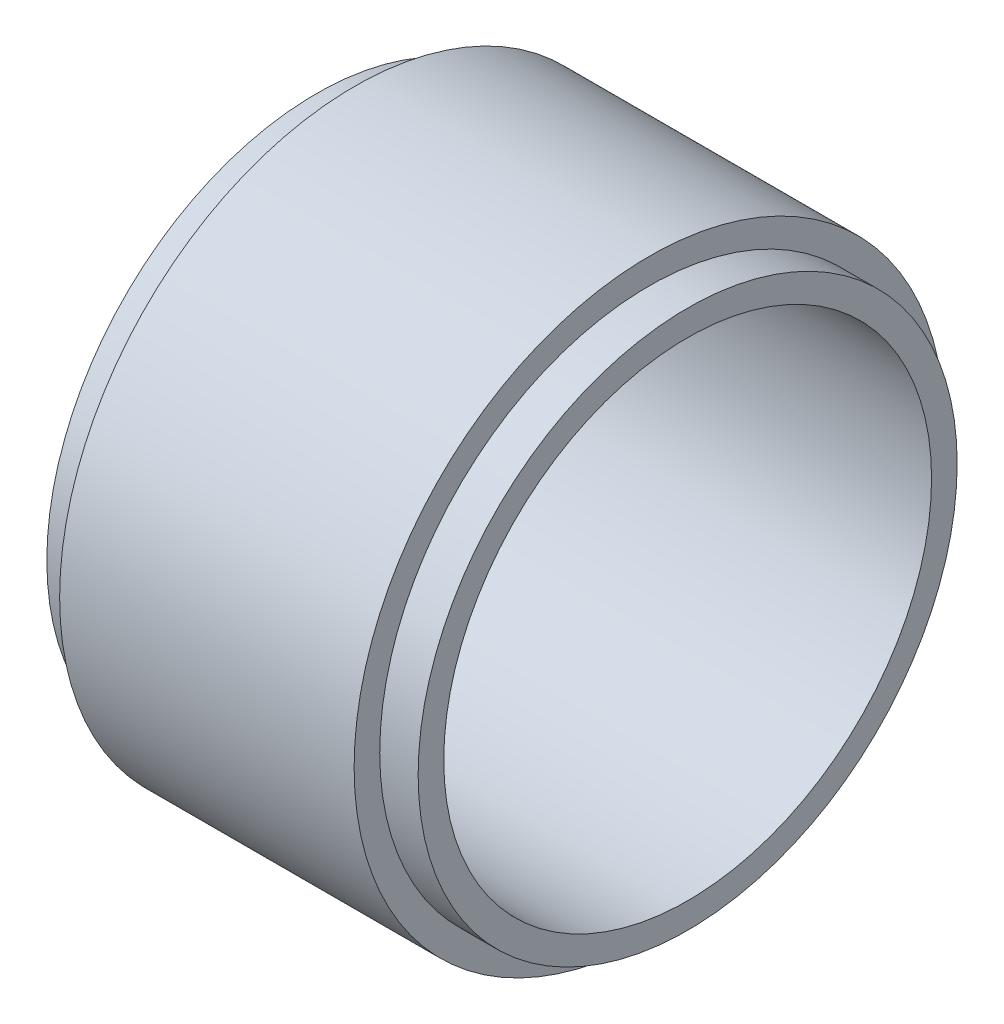
SolidWorks part; units mm, degrees
material "5052-H32"
ref_plane "Front Plane" through (0, 0, 0) normal (0, 0, 1) x (1, 0, 0)
ref_plane "Top Plane" through (0, 0, 0) normal (0, 1, 0) x (1, 0, 0)
ref_plane "Right Plane" through (0, 0, 0) normal (1, 0, 0) x (0, 0, -1)
sketch "Sketch2" plane through (0, 0, 0) normal (0, 0, 1) x (1, 0, 0)
  line L0 (0, 21.05) -> (-3, 21.05)
  line L1 (-3, 21.05) -> (-3, 23.05)
  line L2 (-3, 23.05) -> (-26, 23.05)
  line L3 (-26, 23.05) -> (-26, 21.05)
  line L4 (-26, 21.05) -> (-29, 21.05)
  line L5 (-29, 21.05) -> (-29, 19.05)
  line L6 (-29, 19.05) -> (0, 19.05)
  line L7 (0, 19.05) -> (0, 21.05)
  line L8 (0, 0) -> (-23, 0) construction
  line L9 (0, -22.5996) -> (0, 22.5996) construction
  point P16 (0, 0)
  dimension "D1" = 19.05
  dimension "D2" = 2
  dimension "D3" = 4
  dimension "D4" = 3
  dimension "D5" = 3
  dimension "D6" = 29
revolve "Revolve2" add sketch "Sketch2" angle 360 about L8
